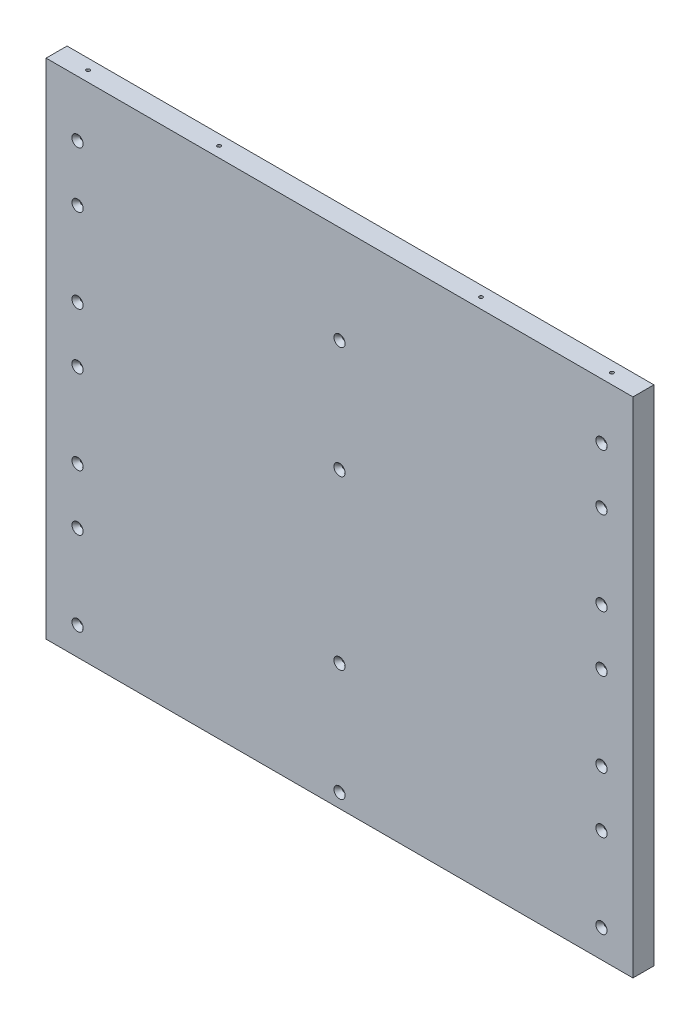
SolidWorks part; units mm, degrees
material "Beech"
ref_plane "Front Plane" through (0, 0, 0) normal (0, 0, 1) x (1, 0, 0)
ref_plane "Top Plane" through (0, 0, 0) normal (0, 1, 0) x (1, 0, 0)
ref_plane "Right Plane" through (0, 0, 0) normal (1, 0, 0) x (0, 0, -1)
sketch "Sketch1" plane through (0, 0, 0) normal (0, 0, 1) x (1, 0, 0)
  line L1 (-266.573, 2683.51) -> (266.573, 2683.51)
  line L2 (-266.573, 2683.51) -> (-266.573, 3140.71)
  line L3 (-266.573, 3140.71) -> (266.573, 3140.71)
  line L4 (266.573, 2683.51) -> (266.573, 3140.71)
  dimension "D1" = 457.2
extrude "Boss-Extrude1" add sketch "Sketch1" against normal blind 19.05
hole_wizard "Hole1" positions "Sketch2" profile "Sketch3" legacy
sketch "Sketch2" plane through (0, 0, 0) normal (0, 0, 1) x (1, 0, 0)
  line L0 (-237.998, 3140.71) -> (-237.998, 2683.51) construction
  line L9 (0, 3140.71) -> (0, 2683.51) construction
  point P13 (-237.998, 3089.91)
  point P15 (-237.998, 3039.11)
  point P17 (-237.998, 2962.91)
  point P19 (-237.998, 2912.11)
  point P21 (-237.998, 2835.91)
  point P23 (-237.998, 2785.11)
  point P25 (-237.998, 2708.91)
  point P38 (237.998, 2708.91)
  point P39 (237.998, 2785.11)
  point P40 (237.998, 2835.91)
  point P41 (237.998, 2912.11)
  point P42 (237.998, 2962.91)
  point P43 (237.998, 3039.11)
  point P44 (237.998, 3089.91)
  point P50 (0, 3051.81)
  point P52 (0, 2950.21)
  point P54 (0, 2797.81)
  point P56 (0, 2696.21)
sketch "Sketch3" plane through (0, 2696.21, 0) normal (1, 0, 0) x (0, -1, 0)
  line L0 (0, 0) -> (0, 51.7539)
  line L1 (0, 51.7539) -> (1.5875, 50.8)
  line L2 (1.5875, 50.8) -> (1.5875, 4.0177)
  line L3 (1.5875, 4.0177) -> (5.08, 0)
  line L4 (5.08, 0) -> (0, 0)
  line L5 (0, -14.3089) -> (0, 102.4216) construction
  line L6 (0, 51.7539) -> (-1.5875, 50.8) construction
  line L7 (-1.5875, 4.0177) -> (-5.08, 0) construction
  dimension "Diameter" = 3.175
  dimension "Depth" = 50.8
  dimension "C-Sink Diameter" = 10.16
  dimension "C-Sink Angle" = 82
  dimension "Drill Angle" = 118
hole_wizard "Hole2" positions "Sketch4" profile "Sketch5" legacy
sketch "Sketch4" plane through (0, 3159.76, -7002.78) normal (0, 1, 0) x (-1, 0, 0)
  line L0 (237.998, 6813.6133) -> (237.998, 7002.78) construction
  line L5 (0, 6813.6133) -> (0, 7002.78) construction
  line L7 (266.573, 6993.255) -> (-266.573, 6993.255) construction
  line L17 (237.998, 6845.5127) -> (237.998, 6958.33)
  line L18 (237.998, 6993.255) -> (0, 6993.255)
  point P30 (237.998, 6993.255)
  point P32 (237.998, 6958.33)
  point P34 (237.998, 6845.5127)
  point P50 (-237.998, 6993.255)
  point P51 (-237.998, 6958.33)
  point P52 (-237.998, 6845.5127)
  point P60 (118.999, 6993.255)
  point P64 (-118.999, 6993.255)
sketch "Sketch5" plane through (118.999, 3159.76, -9.525) normal (1, 0, 0) x (0, 0, 1)
  line L0 (0, 0) -> (0, 39.0539)
  line L1 (0, 39.0539) -> (1.5875, 38.1)
  line L2 (1.5875, 38.1) -> (1.5875, 4.0177)
  line L3 (1.5875, 4.0177) -> (5.08, 0)
  line L4 (5.08, 0) -> (0, 0)
  line L5 (0, -14.3089) -> (0, 102.4216) construction
  line L6 (0, 39.0539) -> (-1.5875, 38.1) construction
  line L7 (-1.5875, 4.0177) -> (-5.08, 0) construction
  dimension "Diameter" = 3.175
  dimension "Depth" = 38.1
  dimension "C-Sink Diameter" = 10.16
  dimension "C-Sink Angle" = 82
  dimension "Drill Angle" = 118
hole_wizard "Hole3" positions "Sketch6" profile "Sketch7" legacy
sketch "Sketch6" plane through (0, 2664.46, -7002.78) normal (0, -1, 0) x (1, 0, 0)
  line L0 (0, 7002.78) -> (0, 5935.98) construction
  line L4 (237.998, 7002.78) -> (237.998, 5935.98) construction
  line L8 (266.573, 6993.255) -> (0, 6993.255) construction
  line L12 (237.998, 6939.28) -> (237.998, 6686.1919)
  point P26 (237.998, 6686.1919)
  point P27 (257.048, 6993.255)
  point P29 (218.948, 6993.255)
  point P31 (19.05, 6993.255)
  point P35 (237.998, 6939.28)
  point P42 (237.998, 6812.7359)
  point P51 (-237.998, 6812.7359)
  point P52 (-237.998, 6939.28)
  point P53 (-19.05, 6993.255)
  point P54 (-218.948, 6993.255)
  point P55 (-257.048, 6993.255)
  point P56 (-237.998, 6686.1919)
sketch "Sketch7" plane through (-237.998, 2664.46, -316.5881) normal (1, 0, 0) x (0, 0, -1)
  line L0 (0, 0) -> (0, 39.0539)
  line L1 (0, 39.0539) -> (1.5875, 38.1)
  line L2 (1.5875, 38.1) -> (1.5875, 4.0177)
  line L3 (1.5875, 4.0177) -> (5.08, 0)
  line L4 (5.08, 0) -> (0, 0)
  line L5 (0, -14.3089) -> (0, 102.4216) construction
  line L6 (0, 39.0539) -> (-1.5875, 38.1) construction
  line L7 (-1.5875, 4.0177) -> (-5.08, 0) construction
  dimension "Diameter" = 3.175
  dimension "Depth" = 38.1
  dimension "C-Sink Diameter" = 10.16
  dimension "C-Sink Angle" = 82
  dimension "Drill Angle" = 118
